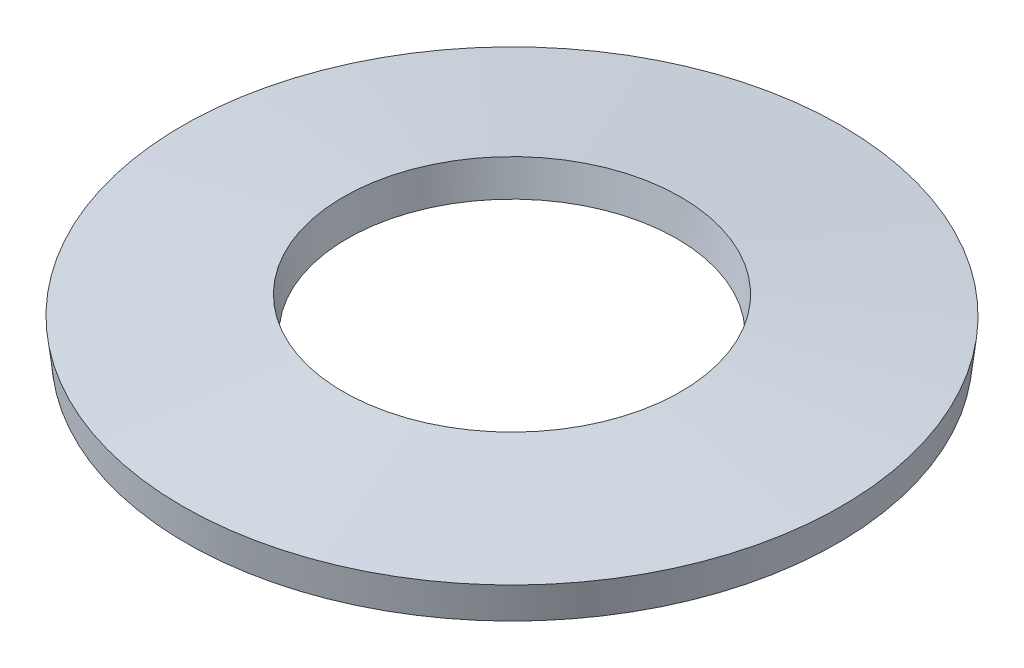
SolidWorks part; units mm, degrees
ref_plane "Front" through (0, 0, 0) normal (0, 0, 1) x (1, 0, 0)
ref_plane "Top" through (0, 0, 0) normal (0, 1, 0) x (1, 0, 0)
ref_plane "Right" through (0, 0, 0) normal (1, 0, 0) x (0, 0, -1)
sketch "Sketch1" plane through (0, 0, 0) normal (0, 0, 1) x (1, 0, 0)
  line L0 (3.1369, 0) -> (1.5875, 0.18)
  line L1 (1.5875, 0.18) -> (1.6256, 0.508)
  line L2 (1.6256, 0.508) -> (3.175, 0.328)
  line L3 (3.175, 0.328) -> (3.1369, 0)
  line L4 (0, 0) -> (0, 0.508) construction
  dimension "ID" = 3.175
  dimension "OD" = 6.35
  dimension "Thickness" = 0.3302
  dimension "Height" = 0.508
revolve "Revolve1" add sketch "Sketch1" angle 360 about L4
